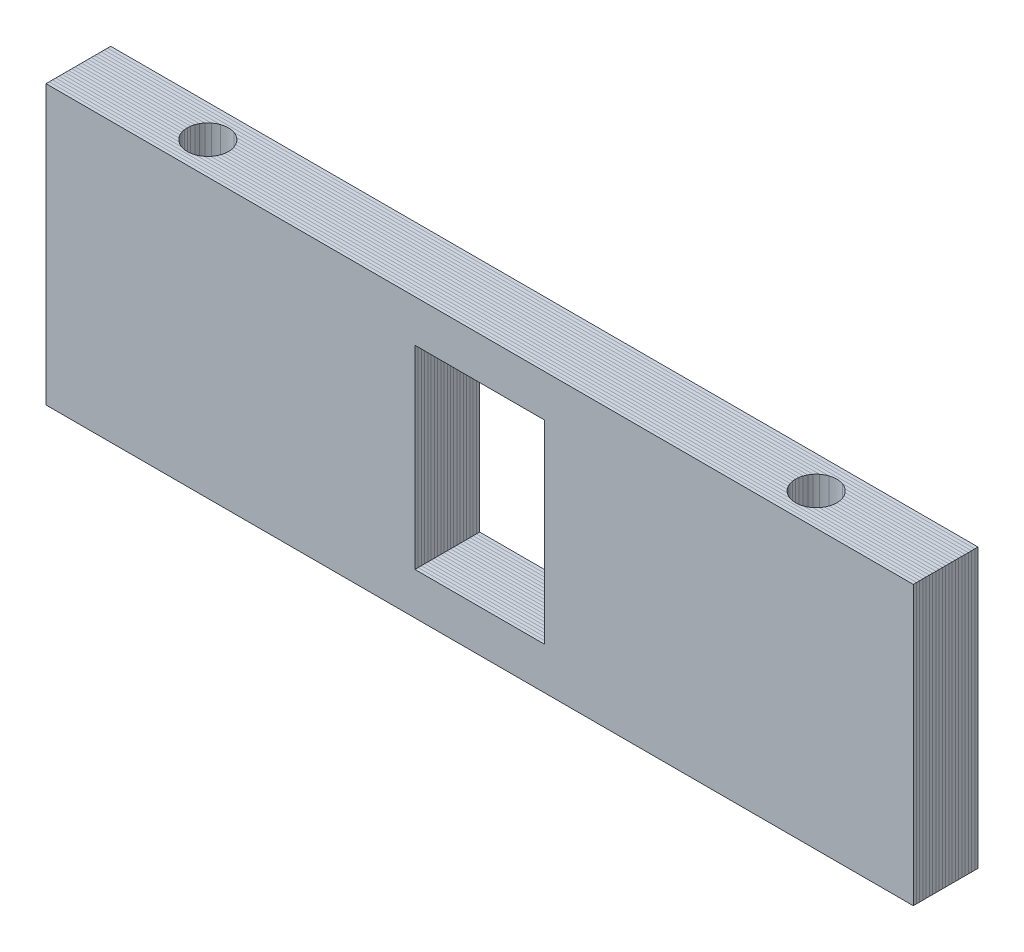
SolidWorks part; units mm, degrees
other "Item de detalhe2"
other "Pasta de soldas"
other "Cordão de solda...2"
material "AISI 304"
ref_plane "Plano frontal" through (0, 0, 0) normal (0, 0, 1) x (1, 0, 0)
ref_plane "Plano superior" through (0, 0, 0) normal (0, 1, 0) x (1, 0, 0)
ref_plane "Plano direito" through (0, 0, 0) normal (1, 0, 0) x (0, 0, -1)
sketch "Esboço1" plane through (0, 0, 0) normal (0, 0, 1) x (1, 0, 0)
  line L1 (0, 0) -> (-134, 0)
  line L2 (0, 0) -> (0, 43)
  line L3 (0, 43) -> (-134, 43)
  line L4 (-134, 0) -> (-134, 43)
  line L5 (-77, 36.5) -> (-57, 36.5)
  line L6 (-77, 36.5) -> (-77, 6.5)
  line L7 (-77, 6.5) -> (-57, 6.5)
  line L8 (-57, 36.5) -> (-57, 6.5)
  dimension "D1" = 43
  dimension "D2" = 134
  dimension "D3" = 30
  dimension "D4" = 20
  dimension "D5" = 6.5
  dimension "D6" = 57
extrude "Ressalto-extrusão1" add sketch "Esboço1" along normal blind 0.5
sketch "Esboço2" plane through (0, 0, 0.5) normal (0, 0, 1) x (1, 0, 0)
  line L1 (-134, 43) -> (0, 43)
  line L2 (-134, 43) -> (-134, 0)
  line L3 (-134, 0) -> (0, 0)
  line L4 (0, 43) -> (0, 0)
  line L5 (-77, 36.5) -> (-57, 36.5)
  line L6 (-77, 36.5) -> (-77, 6.5)
  line L7 (-77, 6.5) -> (-57, 6.5)
  line L8 (-57, 36.5) -> (-57, 6.5)
extrude "Ressalto-extrusão9" add sketch "Esboço2" along normal blind 0.5 separate body
sketch "Esboço7" plane through (0, 0, 1) normal (0, 0, 1) x (1, 0, 0)
  line L1 (-134, 43) -> (0, 43)
  line L2 (-134, 43) -> (-134, 0)
  line L3 (-134, 0) -> (0, 0)
  line L4 (0, 43) -> (0, 0)
  line L5 (-57, 6.5) -> (-77, 6.5)
  line L6 (-57, 6.5) -> (-57, 36.5)
  line L7 (-57, 36.5) -> (-77, 36.5)
  line L8 (-77, 6.5) -> (-77, 36.5)
extrude "Ressalto-extrusão10" add sketch "Esboço7" along normal blind 0.5 separate body
sketch "Esboço8" plane through (0, 0, 1.5) normal (0, 0, 1) x (1, 0, 0)
  line L1 (-134, 43) -> (0, 43)
  line L2 (-134, 43) -> (-134, 0)
  line L3 (-134, 0) -> (0, 0)
  line L4 (0, 43) -> (0, 0)
  line L5 (-57, 6.5) -> (-77, 6.5)
  line L6 (-57, 6.5) -> (-57, 36.5)
  line L7 (-57, 36.5) -> (-77, 36.5)
  line L8 (-77, 6.5) -> (-77, 36.5)
extrude "Ressalto-extrusão11" add sketch "Esboço8" along normal blind 0.5 separate body
sketch "Esboço9" plane through (0, 0, 2) normal (0, 0, 1) x (1, 0, 0)
  line L1 (-134, 43) -> (0, 43)
  line L2 (-134, 43) -> (-134, 0)
  line L3 (-134, 0) -> (0, 0)
  line L4 (0, 43) -> (0, 0)
  line L5 (-77, 36.5) -> (-57, 36.5)
  line L6 (-77, 36.5) -> (-77, 6.5)
  line L7 (-77, 6.5) -> (-57, 6.5)
  line L8 (-57, 36.5) -> (-57, 6.5)
extrude "Ressalto-extrusão12" add sketch "Esboço9" along normal blind 0.5 separate body
sketch "Esboço10" plane through (0, 0, 2.5) normal (0, 0, 1) x (1, 0, 0)
  line L1 (-134, 43) -> (0, 43)
  line L2 (-134, 43) -> (-134, 0)
  line L3 (-134, 0) -> (0, 0)
  line L4 (0, 43) -> (0, 0)
  line L5 (-57, 6.5) -> (-77, 6.5)
  line L6 (-57, 6.5) -> (-57, 36.5)
  line L7 (-57, 36.5) -> (-77, 36.5)
  line L8 (-77, 6.5) -> (-77, 36.5)
extrude "Ressalto-extrusão13" add sketch "Esboço10" along normal blind 0.5 separate body
sketch "Esboço11" plane through (0, 0, 3) normal (0, 0, 1) x (1, 0, 0)
  line L1 (-134, 43) -> (0, 43)
  line L2 (-134, 43) -> (-134, 0)
  line L3 (-134, 0) -> (0, 0)
  line L4 (0, 43) -> (0, 0)
  line L5 (-57, 6.5) -> (-77, 6.5)
  line L6 (-57, 6.5) -> (-57, 36.5)
  line L7 (-57, 36.5) -> (-77, 36.5)
  line L8 (-77, 6.5) -> (-77, 36.5)
extrude "Ressalto-extrusão14" add sketch "Esboço11" along normal blind 0.5 separate body
sketch "Esboço12" plane through (0, 0, 3.5) normal (0, 0, 1) x (1, 0, 0)
  line L1 (-134, 43) -> (0, 43)
  line L2 (-134, 43) -> (-134, 0)
  line L3 (-134, 0) -> (0, 0)
  line L4 (0, 43) -> (0, 0)
  line L5 (-57, 6.5) -> (-77, 6.5)
  line L6 (-57, 6.5) -> (-57, 36.5)
  line L7 (-57, 36.5) -> (-77, 36.5)
  line L8 (-77, 6.5) -> (-77, 36.5)
extrude "Ressalto-extrusão15" add sketch "Esboço12" along normal blind 0.5 separate body
sketch "Esboço13" plane through (0, 0, 4) normal (0, 0, 1) x (1, 0, 0)
  line L1 (-134, 43) -> (0, 43)
  line L2 (-134, 43) -> (-134, 0)
  line L3 (-134, 0) -> (0, 0)
  line L4 (0, 43) -> (0, 0)
  line L5 (-57, 6.5) -> (-77, 6.5)
  line L6 (-57, 6.5) -> (-57, 36.5)
  line L7 (-57, 36.5) -> (-77, 36.5)
  line L8 (-77, 6.5) -> (-77, 36.5)
extrude "Ressalto-extrusão16" add sketch "Esboço13" along normal blind 0.5 separate body
sketch "Esboço14" plane through (0, 0, 4.5) normal (0, 0, 1) x (1, 0, 0)
  line L1 (-134, 43) -> (0, 43)
  line L2 (-134, 43) -> (-134, 0)
  line L3 (-134, 0) -> (0, 0)
  line L4 (0, 43) -> (0, 0)
  line L5 (-77, 36.5) -> (-57, 36.5)
  line L6 (-77, 36.5) -> (-77, 6.5)
  line L7 (-77, 6.5) -> (-57, 6.5)
  line L8 (-57, 36.5) -> (-57, 6.5)
extrude "Ressalto-extrusão17" add sketch "Esboço14" along normal blind 0.5 separate body
sketch "Esboço15" plane through (0, 0, 5) normal (0, 0, 1) x (1, 0, 0)
  line L1 (-134, 43) -> (0, 43)
  line L2 (-134, 43) -> (-134, 0)
  line L3 (-134, 0) -> (0, 0)
  line L4 (0, 43) -> (0, 0)
  line L5 (-57, 6.5) -> (-77, 6.5)
  line L6 (-57, 6.5) -> (-57, 36.5)
  line L7 (-57, 36.5) -> (-77, 36.5)
  line L8 (-77, 6.5) -> (-77, 36.5)
extrude "Ressalto-extrusão18" add sketch "Esboço15" along normal blind 0.5 separate body
sketch "Esboço16" plane through (0, 0, 5.5) normal (0, 0, 1) x (1, 0, 0)
  line L1 (-134, 43) -> (0, 43)
  line L2 (-134, 43) -> (-134, 0)
  line L3 (-134, 0) -> (0, 0)
  line L4 (0, 43) -> (0, 0)
  line L5 (-57, 6.5) -> (-77, 6.5)
  line L6 (-57, 6.5) -> (-57, 36.5)
  line L7 (-57, 36.5) -> (-77, 36.5)
  line L8 (-77, 6.5) -> (-77, 36.5)
extrude "Ressalto-extrusão19" add sketch "Esboço16" along normal blind 0.5 separate body
sketch "Esboço17" plane through (0, 0, 6) normal (0, 0, 1) x (1, 0, 0)
  line L1 (-134, 43) -> (0, 43)
  line L2 (-134, 43) -> (-134, 0)
  line L3 (-134, 0) -> (0, 0)
  line L4 (0, 43) -> (0, 0)
  line L5 (-77, 36.5) -> (-57, 36.5)
  line L6 (-77, 36.5) -> (-77, 6.5)
  line L7 (-77, 6.5) -> (-57, 6.5)
  line L8 (-57, 36.5) -> (-57, 6.5)
extrude "Ressalto-extrusão20" add sketch "Esboço17" along normal blind 0.5 separate body
sketch "Esboço18" plane through (0, 0, 6.5) normal (0, 0, 1) x (1, 0, 0)
  line L1 (-134, 43) -> (0, 43)
  line L2 (-134, 43) -> (-134, 0)
  line L3 (-134, 0) -> (0, 0)
  line L4 (0, 43) -> (0, 0)
  line L5 (-77, 36.5) -> (-57, 36.5)
  line L6 (-77, 36.5) -> (-77, 6.5)
  line L7 (-77, 6.5) -> (-57, 6.5)
  line L8 (-57, 36.5) -> (-57, 6.5)
extrude "Ressalto-extrusão21" add sketch "Esboço18" along normal blind 0.5 separate body
sketch "Esboço19" plane through (0, 0, 7) normal (0, 0, 1) x (1, 0, 0)
  line L1 (-134, 43) -> (0, 43)
  line L2 (-134, 43) -> (-134, 0)
  line L3 (-134, 0) -> (0, 0)
  line L4 (0, 43) -> (0, 0)
  line L5 (-77, 36.5) -> (-57, 36.5)
  line L6 (-77, 36.5) -> (-77, 6.5)
  line L7 (-77, 6.5) -> (-57, 6.5)
  line L8 (-57, 36.5) -> (-57, 6.5)
extrude "Ressalto-extrusão22" add sketch "Esboço19" along normal blind 0.5 separate body
sketch "Esboço20" plane through (0, 0, 7.5) normal (0, 0, 1) x (1, 0, 0)
  line L1 (-134, 43) -> (0, 43)
  line L2 (-134, 43) -> (-134, 0)
  line L3 (-134, 0) -> (0, 0)
  line L4 (0, 43) -> (0, 0)
  line L5 (-57, 6.5) -> (-77, 6.5)
  line L6 (-57, 6.5) -> (-57, 36.5)
  line L7 (-57, 36.5) -> (-77, 36.5)
  line L8 (-77, 6.5) -> (-77, 36.5)
extrude "Ressalto-extrusão23" add sketch "Esboço20" along normal blind 0.5 separate body
sketch "Esboço21" plane through (0, 0, 8) normal (0, 0, 1) x (1, 0, 0)
  line L1 (-134, 43) -> (0, 43)
  line L2 (-134, 43) -> (-134, 0)
  line L3 (-134, 0) -> (0, 0)
  line L4 (0, 43) -> (0, 0)
  line L5 (-77, 36.5) -> (-57, 36.5)
  line L6 (-77, 36.5) -> (-77, 6.5)
  line L7 (-77, 6.5) -> (-57, 6.5)
  line L8 (-57, 36.5) -> (-57, 6.5)
extrude "Ressalto-extrusão24" add sketch "Esboço21" along normal blind 0.5 separate body
sketch "Esboço22" plane through (0, 0, 8.5) normal (0, 0, 1) x (1, 0, 0)
  line L1 (-134, 43) -> (0, 43)
  line L2 (-134, 43) -> (-134, 0)
  line L3 (-134, 0) -> (0, 0)
  line L4 (0, 43) -> (0, 0)
  line L5 (-77, 36.5) -> (-57, 36.5)
  line L6 (-77, 36.5) -> (-77, 6.5)
  line L7 (-77, 6.5) -> (-57, 6.5)
  line L8 (-57, 36.5) -> (-57, 6.5)
extrude "Ressalto-extrusão25" add sketch "Esboço22" along normal blind 0.5 separate body
sketch "Esboço23" plane through (0, 0, 9) normal (0, 0, 1) x (1, 0, 0)
  line L1 (-134, 43) -> (0, 43)
  line L2 (-134, 43) -> (-134, 0)
  line L3 (-134, 0) -> (0, 0)
  line L4 (0, 43) -> (0, 0)
  line L5 (-57, 6.5) -> (-77, 6.5)
  line L6 (-57, 6.5) -> (-57, 36.5)
  line L7 (-57, 36.5) -> (-77, 36.5)
  line L8 (-77, 6.5) -> (-77, 36.5)
extrude "Ressalto-extrusão26" add sketch "Esboço23" along normal blind 0.5 separate body
sketch "Esboço24" plane through (0, 0, 9.5) normal (0, 0, 1) x (1, 0, 0)
  line L1 (-134, 43) -> (0, 43)
  line L2 (-134, 43) -> (-134, 0)
  line L3 (-134, 0) -> (0, 0)
  line L4 (0, 43) -> (0, 0)
  line L5 (-77, 36.5) -> (-57, 36.5)
  line L6 (-77, 36.5) -> (-77, 6.5)
  line L7 (-77, 6.5) -> (-57, 6.5)
  line L8 (-57, 36.5) -> (-57, 6.5)
extrude "Ressalto-extrusão27" add sketch "Esboço24" along normal blind 0.5 separate body
hole_wizard "Broca de rosquear para tarraxa de M3x0.51" positions "Esboço25" profile "Esboço27" hole size "M3x0.5" standard "Ansi Metric"
sketch "Esboço25" plane through (0, 43, 0) normal (0, 1, 0) x (1, 0, 0)
  line L0 (-134, -5) -> (-134, -4.5) construction
  line L1 (0, -10) -> (-134, -10) construction
  point P0 (-114, -5)
  point P2 (-20, -5)
  dimension "D1" = 20
  dimension "D2" = 5
  dimension "D3" = 20
  dimension "D4" = 5
sketch "Esboço27" plane through (-114, 43, 5) normal (1, 0, 0) x (0, 0, 1)
  line L0 (0, 0) -> (0, 25.4)
  line L1 (0, 25.4) -> (3.175, 23.4923)
  line L2 (3.175, 23.4923) -> (3.175, 0)
  line L5 (3.175, 0) -> (0, 0)
  line L10 (0, 25.4) -> (-3.175, 23.4923) construction
  line L11 (0, -6.35) -> (0, 107.95) construction
  dimension "Hole Dia." = 6.35
  dimension "Hole Depth" = 25.4
  dimension "Drill Angle" = 118
